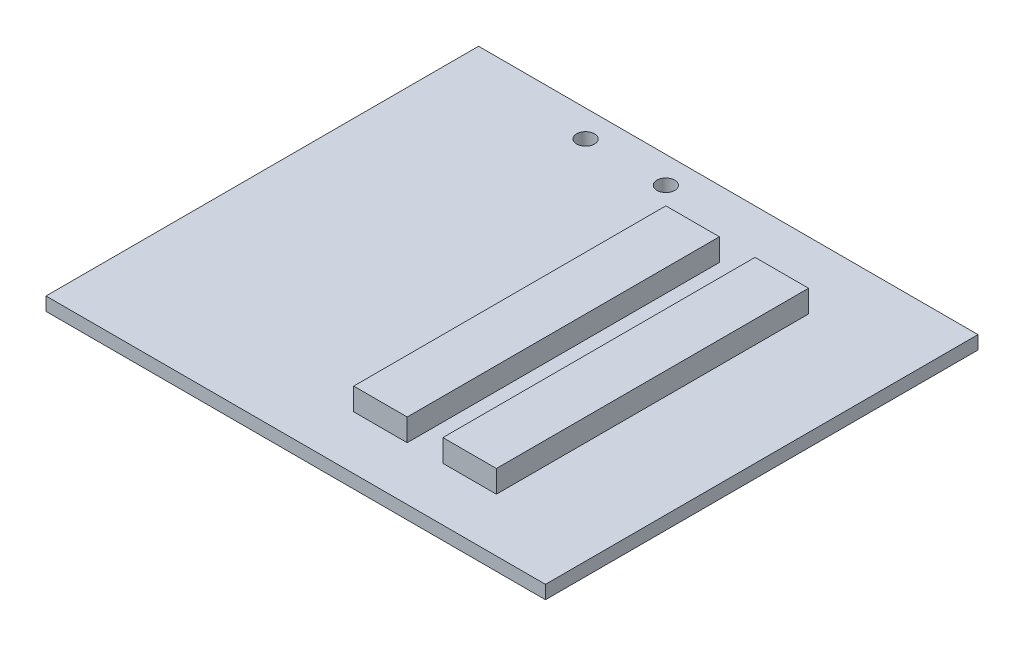
SolidWorks part; units mm, degrees
ref_plane "Front" through (0, 0, 0) normal (0, 0, 1) x (1, 0, 0)
ref_plane "Top" through (0, 0, 0) normal (0, 1, 0) x (1, 0, 0)
ref_plane "Right" through (0, 0, 0) normal (1, 0, 0) x (0, 0, -1)
sketch "Эскиз1" plane through (0, 0, 0) normal (0, 1, 0) x (1, 0, 0)
  line L1 (-28, 24.25) -> (28, 24.25)
  line L2 (-28, 24.25) -> (-28, -24.25)
  line L3 (-28, -24.25) -> (28, -24.25)
  line L4 (28, 24.25) -> (28, -24.25)
  line L5 (-28, 24.25) -> (28, -24.25) construction
  line L6 (-28, -24.25) -> (28, 24.25) construction
  circle A0 centre (-13, 21.25) radius 1
  circle A1 centre (-4, 21.25) radius 1
  point P0 (0, 0)
  dimension "D3" = 2
  dimension "D1" = 56
  dimension "D2" = 48.5
  dimension "D4" = 15
  dimension "D5" = 9
  dimension "D6" = 3
extrude "Бобышка-Вытянуть1" add sketch "Эскиз1" along normal blind 1.5
sketch "Эскиз2" plane through (0, 1.5, 0) normal (0, 1, 0) x (1, 0, 0)
  line L0 (28, 24.25) -> (-28, 24.25) construction
  line L1 (0.5, 16.75) -> (6.5, 16.75)
  line L2 (0.5, 16.75) -> (0.5, -18.25)
  line L3 (0.5, -18.25) -> (6.5, -18.25)
  line L4 (6.5, 16.75) -> (6.5, -18.25)
  line L5 (10.5, 16.75) -> (16.5, 16.75)
  line L6 (10.5, 16.75) -> (10.5, -18.25)
  line L7 (10.5, -18.25) -> (16.5, -18.25)
  line L8 (16.5, 16.75) -> (16.5, -18.25)
  line L9 (28, -24.25) -> (28, 24.25) construction
  dimension "D1" = 6
  dimension "D2" = 35
  dimension "D3" = 4
  dimension "D4" = 7.5
  dimension "D5" = 11.5
extrude "Бобышка-Вытянуть2" add sketch "Эскиз2" along normal blind 2.5
sketch "Эскиз3" plane through (0, 0, 0) normal (0, -1, 0) x (1, 0, 0)
  line L0 (28, -24.25) -> (-28, -24.25) construction
  line L1 (-22.5, -1.25) -> (-28.5, -1.25)
  line L2 (-22.5, -1.25) -> (-22.5, -13.25)
  line L3 (-22.5, -13.25) -> (-28.5, -13.25)
  line L4 (-28.5, -1.25) -> (-28.5, -13.25)
  line L5 (-28, -24.25) -> (-28, 24.25) construction
  dimension "D1" = 6
  dimension "D2" = 12
  dimension "D3" = 11
  dimension "D4" = 0.5
extrude "Бобышка-Вытянуть3" add sketch "Эскиз3" along normal blind 4.5
